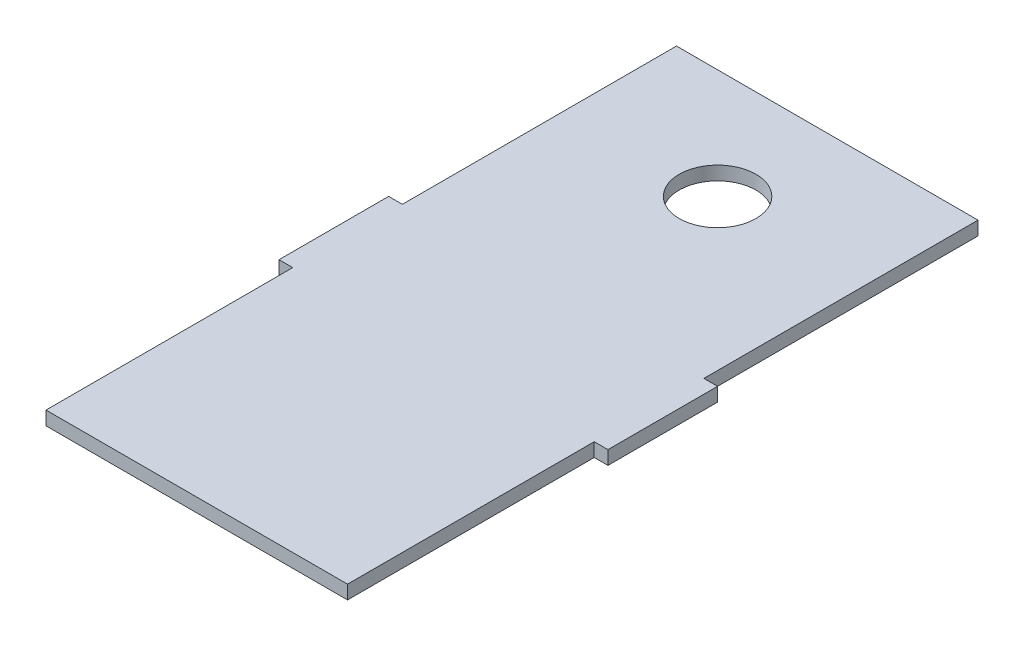
SolidWorks part; units mm, degrees
ref_plane "Front Plane" through (0, 0, 0) normal (0, 0, 1) x (1, 0, 0)
ref_plane "Top Plane" through (0, 0, 0) normal (0, 1, 0) x (1, 0, 0)
ref_plane "Right Plane" through (0, 0, 0) normal (1, 0, 0) x (0, 0, -1)
sketch "Sketch1" plane through (0, 0, 0) normal (0, 1, 0) x (1, 0, 0)
  line L0 (38.1, 146.05) -> (38.1, 120.65) construction
  line L1 (0, 0) -> (76.2, 0)
  line L2 (0, 0) -> (0, 146.05)
  line L3 (0, 146.05) -> (76.2, 146.05)
  line L4 (76.2, 0) -> (76.2, 146.05)
  circle A0 centre (38.1, 120.65) radius 8.89
  dimension "D4" = 17.78
  dimension "D1" = 146.05
  dimension "D2" = 76.2
  dimension "D3" = 25.4
extrude "Boss-Extrude1" add sketch "Sketch1" along normal blind 3.175
sketch "Sketch2" plane through (0, 3.175, 0) normal (0, 1, 0) x (1, 0, 0)
  line L1 (0, 0) -> (3.175, 0)
  line L2 (0, 0) -> (0, 57.15)
  line L3 (0, 57.15) -> (3.175, 57.15)
  line L4 (3.175, 0) -> (3.175, 57.15)
  line L5 (0, 146.05) -> (3.175, 146.05)
  line L6 (0, 146.05) -> (0, 82.55)
  line L7 (0, 82.55) -> (3.175, 82.55)
  line L8 (3.175, 146.05) -> (3.175, 82.55)
  line L9 (76.2, 146.05) -> (73.025, 146.05)
  line L10 (76.2, 146.05) -> (76.2, 82.55)
  line L11 (76.2, 82.55) -> (73.025, 82.55)
  line L12 (73.025, 146.05) -> (73.025, 82.55)
  line L13 (76.2, 0) -> (73.025, 0)
  line L14 (76.2, 0) -> (76.2, 57.15)
  line L15 (76.2, 57.15) -> (73.025, 57.15)
  line L16 (73.025, 0) -> (73.025, 57.15)
  dimension "D1" = 25.4
  dimension "D2" = 63.5
  dimension "D3" = 3.175
  dimension "D4" = 3.175
  dimension "D5" = 3.175
  dimension "D6" = 3.175
  dimension "D7" = 25.4
  dimension "D8" = 63.5
extrude "Cut-Extrude1" cut sketch "Sketch2" against normal blind 3.175
